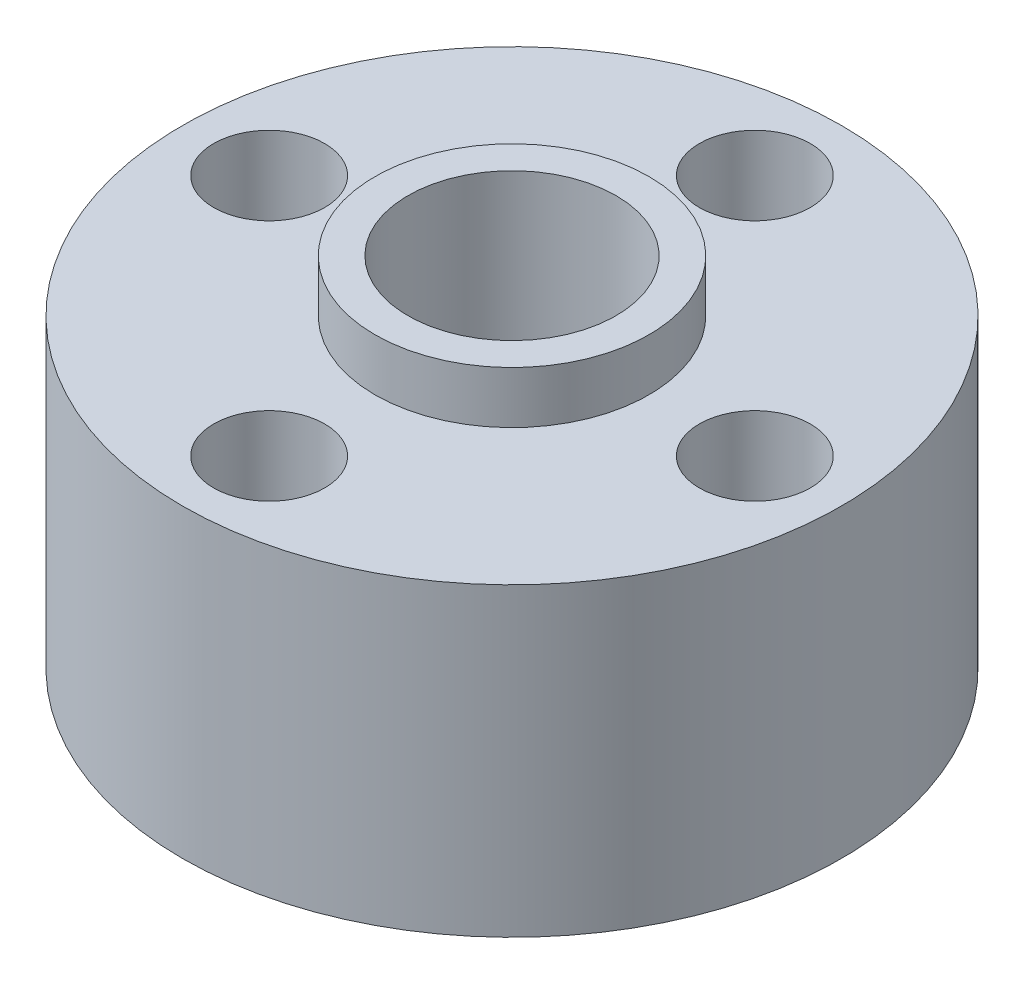
SolidWorks part; units mm, degrees
material "6061 合金"
ref_plane "前视基准面" through (0, 0, 0) normal (0, 0, 1) x (1, 0, 0)
ref_plane "上视基准面" through (0, 0, 0) normal (0, 1, 0) x (1, 0, 0)
ref_plane "右视基准面" through (0, 0, 0) normal (1, 0, 0) x (0, 0, -1)
ref_plane "基准面4" through (0, 0, 0) normal (0, 0, -1) x (-1, 0, 0)
sketch "草图1" plane through (0, 0, 0) normal (0, 0, -1) x (-1, 0, 0)
  line L0 (-9.5, -4.375) -> (0, -4.375)
  line L1 (0, -4.375) -> (0, 4.425)
  line L2 (0, 4.425) -> (-9.5, 4.425)
  line L3 (-9.5, 4.425) -> (-9.5, -4.375)
  line L4 (0, -4.375) -> (0, 4.425) construction
revolve "旋转1" add sketch "草图1" angle 360 about L4
sketch "草图2" plane through (0, 4.425, 0) normal (0, 1, 0) x (-1, 0, 0)
  circle A0 centre (0, 0) radius 3.95
extrude "凸台-拉伸1" add sketch "草图2" along normal blind 1.5
sketch "草图3" plane through (0, -4.375, 0) normal (0, -1, 0) x (1, 0, 0)
  circle A0 centre (0, 0) radius 3.95
extrude "凸台-拉伸2" add sketch "草图3" along normal blind 1.5
hole_wizard "Ø3.2 (3.2) 直径孔1" positions "草图5" profile "草图4" hole size "Ø3.2" standard "ANSI Metric"
sketch "草图5" plane through (0, -4.375, 0) normal (0, -1, 0) x (-1, 0, 0)
  point P0 (0, 7)
  point P1 (-7, 0)
  point P2 (0, -7)
  point P3 (7, 0)
sketch "草图4" plane through (0, -4.375, -7) normal (1, 0, 0) x (0, 0, -1)
  line L0 (0, 0) -> (0, 10.3)
  line L1 (0, 10.3) -> (1.6, 10.3)
  line L2 (1.6, 10.3) -> (1.6, 0)
  line L5 (1.6, 0) -> (0, 0)
  line L11 (0, -6.35) -> (0, 107.95) construction
  dimension "通孔孔直径" = 3.2
  dimension "通孔孔深度" = 10.3
hole_wizard "Ø6.0 (6) 直径孔1" positions "草图7" profile "草图6" hole size "Ø6.0" standard "ANSI Metric"
sketch "草图7" plane through (0, -5.875, 0) normal (0, -1, 0) x (-1, 0, 0)
  point P0 (0, 0)
sketch "草图6" plane through (0, -5.875, 0) normal (1, 0, 0) x (0, 0, -1)
  line L0 (0, 0) -> (0, 11.8)
  line L1 (0, 11.8) -> (3, 11.8)
  line L2 (3, 11.8) -> (3, 0)
  line L5 (3, 0) -> (0, 0)
  line L11 (0, -6.35) -> (0, 107.95) construction
  dimension "通孔孔直径" = 6
  dimension "通孔孔深度" = 11.8
